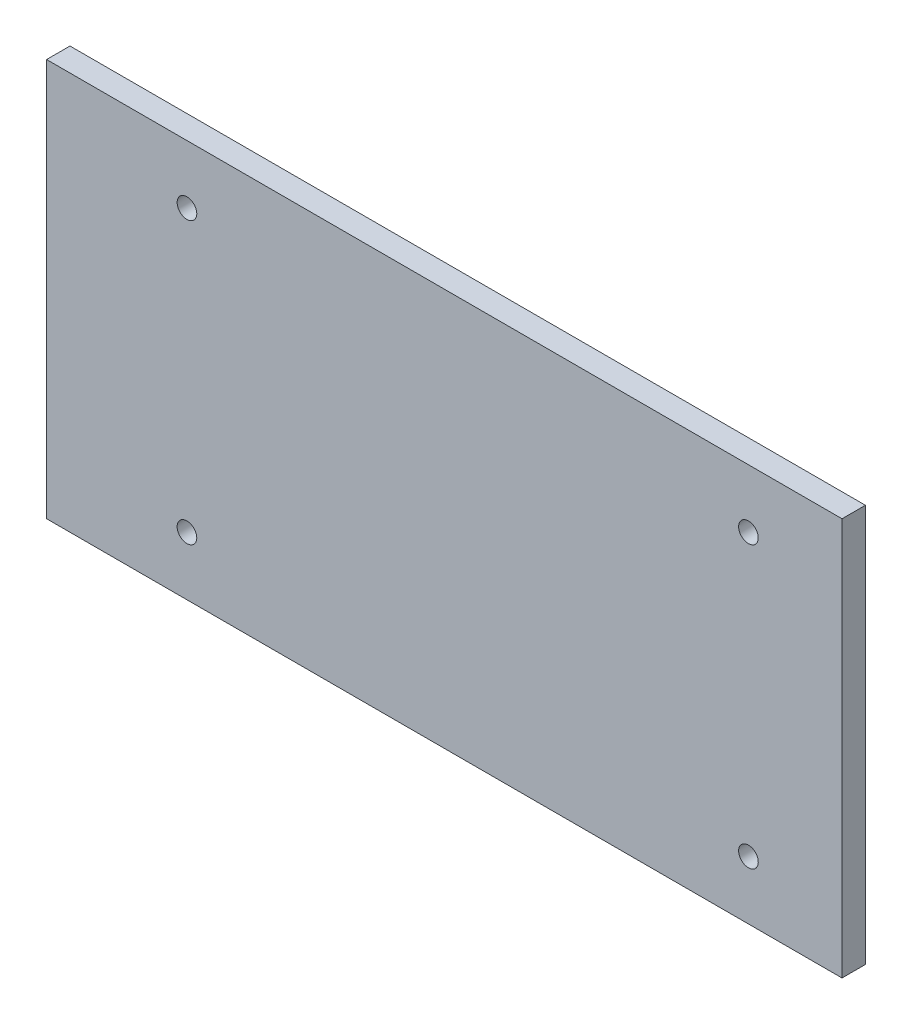
SolidWorks part; units mm, degrees
ref_plane "Front Plane" through (0, 0, 0) normal (1, 0, 0) x (0, 1, 0)
ref_plane "Top Plane" through (0, 0, 0) normal (0, 0, 1) x (0, 1, 0)
ref_plane "Right Plane" through (0, 0, 0) normal (0, 1, 0) x (-1, 0, 0)
sketch "Sketch1" plane through (0, 0, 0) normal (0, 0, 1) x (0, 1, 0)
  line L0 (0, -1000) -> (0, 49000) construction
  line L1 (-42.5, -85) -> (42.5, -85)
  line L2 (-42.5, -85) -> (-42.5, 85)
  line L3 (-42.5, 85) -> (42.5, 85)
  line L4 (42.5, -85) -> (42.5, 85)
  line L5 (-42.5, -85) -> (42.5, 85) construction
  line L6 (-42.5, 85) -> (42.5, -85) construction
  line L7 (-1000, 0) -> (49000, 0) construction
  circle A0 centre (-30, 55) radius 2.1
  circle A1 centre (-30, -65) radius 2.1
  circle A2 centre (30, -65) radius 2.1
  circle A3 centre (30, 55) radius 2.1
  point P0 (0, 0)
  dimension "D5" = 4.2
  dimension "D8" = 4.2
  dimension "D1" = 85
  dimension "D2" = 170
  dimension "D3" = 30
  dimension "D4" = 30
  dimension "D6" = 120
  dimension "D7" = 30
extrude "Boss-Extrude1" add sketch "Sketch1" along normal blind 5
